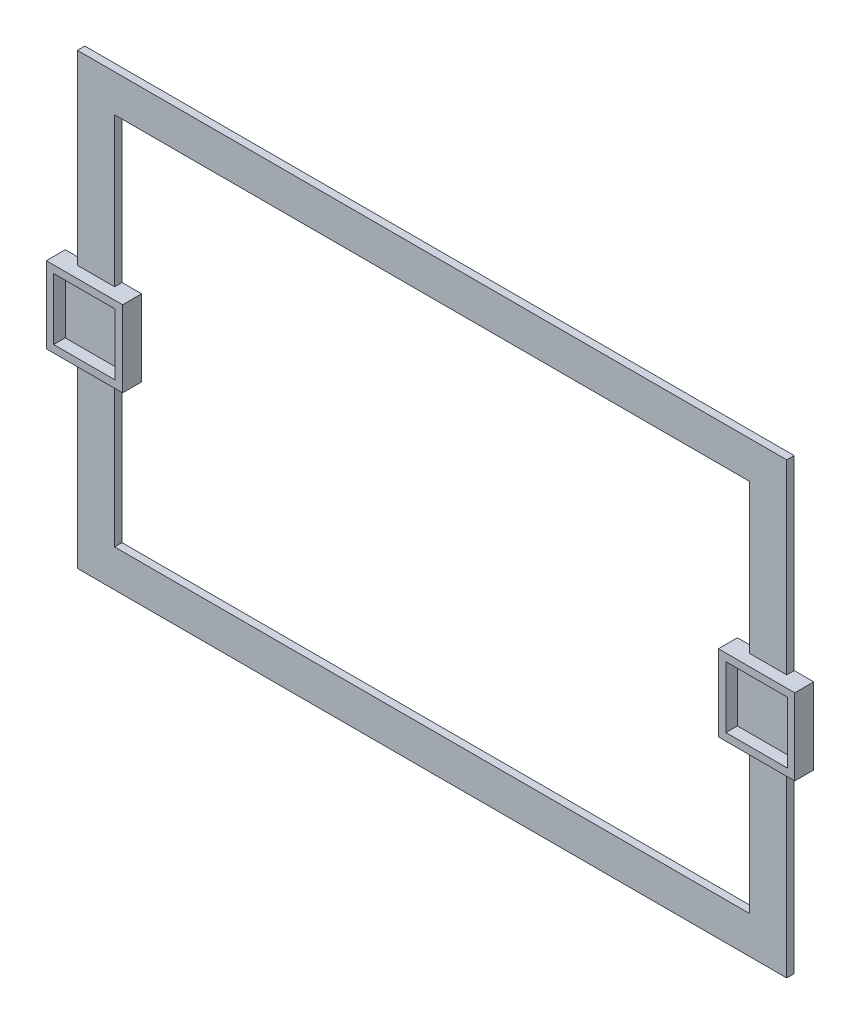
SolidWorks part; units mm, degrees
ref_plane "Front Plane" through (0, 0, 0) normal (0, 0, 1) x (1, 0, 0)
ref_plane "Top Plane" through (0, 0, 0) normal (0, 1, 0) x (1, 0, 0)
ref_plane "Right Plane" through (0, 0, 0) normal (1, 0, 0) x (0, 0, -1)
sketch "Sketch1" plane through (0, 0, 0) normal (0, 0, 1) x (1, 0, 0)
  line L1 (0, 0) -> (41.91, 0)
  line L2 (0, 0) -> (0, 41.91)
  line L3 (0, 41.91) -> (41.91, 41.91)
  line L4 (41.91, 0) -> (41.91, 41.91)
  line L5 (-5.08, 46.99) -> (46.99, 46.99)
  line L6 (-5.08, 46.99) -> (-5.08, -5.08)
  line L7 (-5.08, -5.08) -> (46.99, -5.08)
  line L8 (46.99, 46.99) -> (46.99, -5.08)
  line L9 (458.47, 41.91) -> (500.38, 41.91)
  line L10 (458.47, 41.91) -> (458.47, 0)
  line L11 (458.47, 0) -> (500.38, 0)
  line L12 (500.38, 41.91) -> (500.38, 0)
  line L13 (453.39, 46.99) -> (505.46, 46.99)
  line L14 (453.39, 46.99) -> (453.39, -5.08)
  line L15 (453.39, -5.08) -> (505.46, -5.08)
  line L16 (505.46, 46.99) -> (505.46, -5.08)
  point P17 (458.47, 20.955)
  dimension "D1" = 41.91
  dimension "D2" = 41.91
  dimension "D3" = 5.08
  dimension "D4" = 5.08
  dimension "D5" = 5.08
  dimension "D6" = 5.08
  dimension "D7" = 41.91
  dimension "D8" = 41.91
  dimension "D9" = 5.08
  dimension "D10" = 5.08
  dimension "D11" = 406.4
extrude "Boss-Extrude1" add sketch "Sketch1" along normal blind 7.874
sketch "Sketch2" plane through (0, 0, 0) normal (0, 0, -1) x (-1, 0, 0)
  line L0 (-46.99, 46.99) -> (5.08, 46.99) construction
  line L10 (-8.255, -5.08) -> (-8.255, -132.08)
  line L11 (-8.255, -132.08) -> (-33.655, -132.08)
  line L12 (-33.655, -5.08) -> (-33.655, -106.68)
  line L15 (-365.125, -132.08) -> (-390.525, -132.08)
  line L25 (-33.655, -132.08) -> (-365.125, -132.08)
  line L27 (-33.655, -106.68) -> (-365.125, -106.68)
  line L34 (-8.255, 46.99) -> (-8.255, 173.99)
  line L35 (-8.255, 173.99) -> (-33.655, 173.99)
  line L40 (-365.125, 173.99) -> (-391.5985, 173.99)
  line L54 (-33.655, 173.99) -> (-365.125, 173.99)
  line L55 (-33.655, 46.99) -> (-33.655, 148.59)
  line L56 (-33.655, 148.59) -> (-33.655, 46.99)
  line L57 (-466.725, 46.99) -> (-466.725, 148.59)
  line L58 (-365.125, 148.59) -> (-33.655, 148.59)
  line L59 (-505.46, 46.99) -> (-453.39, 46.99) construction
  line L61 (-8.255, 46.99) -> (-33.655, 46.99)
  line L62 (-8.255, -5.08) -> (-33.655, -5.08)
  line L63 (5.08, -5.08) -> (-46.99, -5.08) construction
  line L64 (-466.725, 148.59) -> (-365.125, 148.59)
  line L65 (-453.39, 46.99) -> (-453.39, -5.08) construction
  line L67 (-492.125, 46.99) -> (-492.125, 173.99)
  line L68 (-492.125, 173.99) -> (-391.5985, 173.99)
  line L69 (-466.725, 46.99) -> (-492.125, 46.99)
  line L70 (-466.725, -5.08) -> (-466.725, -106.68)
  line L71 (-453.39, -5.08) -> (-505.46, -5.08) construction
  line L72 (-466.725, -106.68) -> (-365.125, -106.68)
  line L73 (-492.125, -5.08) -> (-492.125, -132.08)
  line L74 (-492.125, -132.08) -> (-390.525, -132.08)
  line L75 (-466.725, -5.08) -> (-492.125, -5.08)
  dimension "D1" = 127
  dimension "D2" = 25.4
  dimension "D3" = 127
  dimension "D4" = 25.4
  dimension "D5" = 13.335
  dimension "D6" = 101.6
  dimension "D7" = 0
  dimension "D8" = 25.4
  dimension "D9" = 25.4
  dimension "D10" = 331.47
extrude "Boss-Extrude3" add sketch "Sketch2" along normal blind 5.08 separate body
sketch "Sketch3" plane through (0, 0, 0) normal (0, 0, -1) x (-1, 0, 0)
  line L1 (5.08, -5.08) -> (-46.99, -5.08)
  line L2 (5.08, -5.08) -> (5.08, 46.99)
  line L3 (5.08, 46.99) -> (-46.99, 46.99)
  line L4 (-46.99, -5.08) -> (-46.99, 46.99)
  line L5 (-453.39, -5.08) -> (-505.46, -5.08)
  line L6 (-453.39, -5.08) -> (-453.39, 46.99)
  line L7 (-453.39, 46.99) -> (-505.46, 46.99)
  line L8 (-505.46, -5.08) -> (-505.46, 46.99)
extrude "Boss-Extrude4" add sketch "Sketch3" along normal blind 5.08
